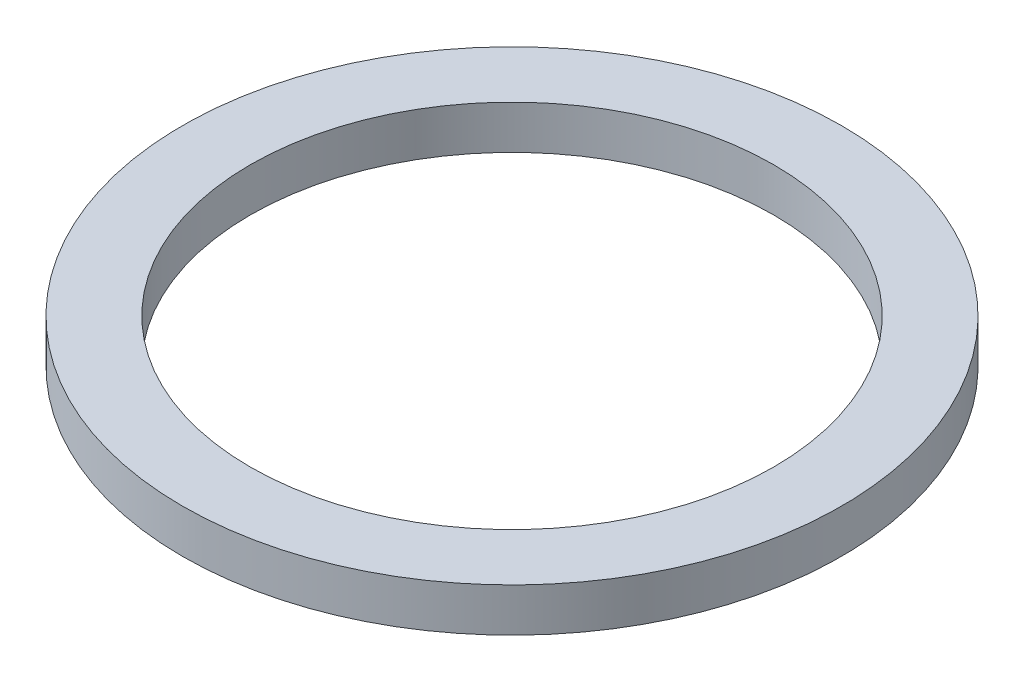
SolidWorks part; units mm, degrees
ref_plane "Front" through (0, 0, 0) normal (0, 0, 1) x (1, 0, 0)
ref_plane "Top" through (0, 0, 0) normal (0, 1, 0) x (1, 0, 0)
ref_plane "Right" through (0, 0, 0) normal (1, 0, 0) x (0, 0, -1)
sketch "Sketch2" plane through (0, 0, 0) normal (0, 1, 0) x (1, 0, 0)
  circle A0 centre (0, 0) radius 13.462
  dimension "D1" = 26.924
extrude "Boss-Extrude1" add sketch "Sketch2" along normal blind 1.778
sketch "Sketch3" plane through (0, 1.778, 0) normal (0, 1, 0) x (1, 0, 0)
  circle A0 centre (0, 0) radius 10.6934
  dimension "D1" = 21.3868
extrude "Cut-Extrude1" cut sketch "Sketch3" against normal through all
